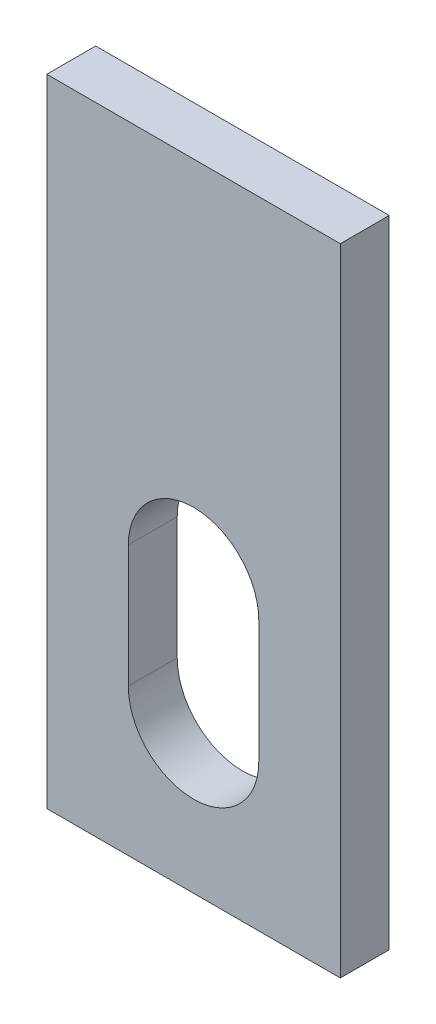
SolidWorks part; units mm, degrees
ref_plane "前视基准面" through (0, 0, 0) normal (0, 0, 1) x (1, 0, 0)
ref_plane "上视基准面" through (0, 0, 0) normal (0, 1, 0) x (1, 0, 0)
ref_plane "右视基准面" through (0, 0, 0) normal (1, 0, 0) x (0, 0, -1)
sketch "草图1" plane through (0, 0, 0) normal (0, 0, 1) x (1, 0, 0)
  line L0 (30, -130) -> (30, -100) construction
  line L1 (0, 0) -> (60, 0)
  line L2 (0, 0) -> (0, -130)
  line L3 (0, -130) -> (60, -130)
  line L4 (60, 0) -> (60, -130)
  line L5 (30, -100) -> (30, -75) construction
  line L6 (30, -100) -> (30, -75) construction
  line L7 (16.6625, -100) -> (16.6625, -75)
  line L8 (43.3375, -100) -> (43.3375, -75)
  arc A0 (16.6625, -100) -> (43.3375, -100) centre (30, -100) ccw
  arc A1 (43.3375, -75) -> (16.6625, -75) centre (30, -75) ccw
  point P7 (30, -87.5)
extrude "凸台-拉伸3" add sketch "草图1" along normal blind 10
